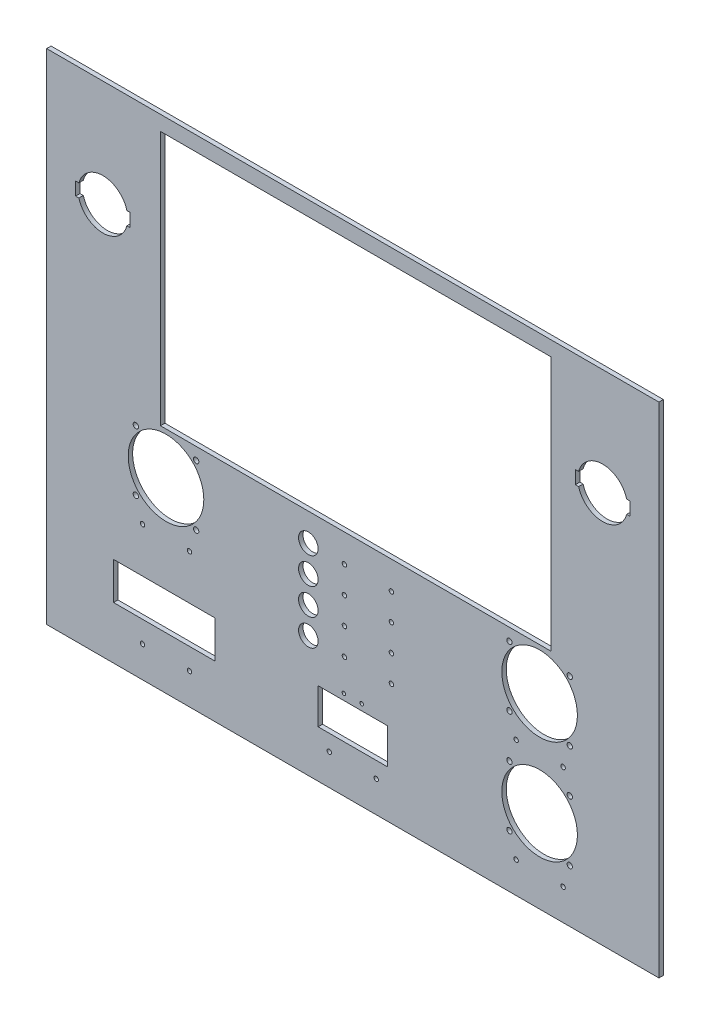
SolidWorks part; units mm, degrees
material "PE High Density"
ref_plane "Front Plane" through (0, 0, 0) normal (0, 0, 1) x (1, 0, 0)
ref_plane "Top Plane" through (0, 0, 0) normal (0, 1, 0) x (1, 0, 0)
ref_plane "Right Plane" through (0, 0, 0) normal (1, 0, 0) x (0, 0, -1)
sketch "Sketch1" plane through (0, 0, 0) normal (0, 0, 1) x (1, 0, 0)
  line L8 (-5.2959, -714.9465) -> (868.8959, -714.9465)
  line L9 (-5.2959, -2.8321) -> (868.8959, -2.8321)
  line L10 (-5.2959, -2.8321) -> (-5.2959, -714.9465)
  line L11 (868.8959, -714.9465) -> (868.8959, -2.8321)
  dimension "D1" = 712.1144
  dimension "D2" = 874.1918
  dimension "D3" = 2.8321
  dimension "D4" = 5.2959
extrude "Boss-Extrude1" add sketch "Sketch1" along normal blind 6.35
sketch "Sketch2" plane through (0, 0, 6.35) normal (0, 0, 1) x (1, 0, 0)
  line L0 (-5.2959, -714.9465) -> (868.8959, -714.9465) construction
  line L1 (868.8959, -714.9465) -> (868.8959, -2.8321) construction
  circle A0 centre (165.1381, -448.3735) radius 53.975
  circle A1 centre (698.5381, -448.3735) radius 53.975
  circle A2 centre (698.5381, -596.4555) radius 53.975
  dimension "D5" = 107.95
  dimension "D1" = 148.082
  dimension "D2" = 118.491
  dimension "D3" = 170.3578
  dimension "D4" = 533.4
extrude "Cut-Extrude1" cut sketch "Sketch2" against normal through all
sketch "Sketch3" plane through (0, 0, 6.35) normal (0, 0, 1) x (1, 0, 0)
  line L0 (-5.2959, -2.8321) -> (-5.2959, -714.9465) construction
  line L1 (-5.2959, -714.9465) -> (868.8959, -714.9465) construction
  circle A0 centre (122.0851, -405.3205) radius 3.81
  circle A2 centre (208.1911, -491.4265) radius 3.81
  circle A3 centre (122.0851, -491.4265) radius 3.81
  circle A4 centre (741.5911, -405.3205) radius 3.81
  circle A5 centre (655.4851, -405.3205) radius 3.81
  circle A6 centre (655.4851, -491.4265) radius 3.81
  circle A7 centre (741.5911, -491.4265) radius 3.81
  circle A8 centre (741.5911, -553.4025) radius 3.81
  circle A9 centre (655.4851, -553.4025) radius 3.81
  circle A10 centre (655.4851, -639.5085) radius 3.81
  circle A11 centre (741.5911, -639.5085) radius 3.81
  circle A12 centre (208.1911, -405.3205) radius 3.81
  dimension "D1" = 7.62
  dimension "D2" = 86.106
  dimension "D3" = 86.106
  dimension "D4" = 127.381
  dimension "D5" = 223.52
  dimension "D6" = 447.294
  dimension "D7" = 86.106
  dimension "D8" = 61.976
  dimension "D9" = 86.106
extrude "Cut-Extrude2" cut sketch "Sketch3" against normal through all
sketch "Sketch4" plane through (0, 0, 6.35) normal (0, 0, 1) x (1, 0, 0)
  line L0 (-5.2959, -714.9465) -> (868.8959, -714.9465) construction
  line L1 (868.8959, -714.9465) -> (868.8959, -2.8321) construction
  circle A0 centre (368.3381, -427.6725) radius 13.97
  circle A1 centre (368.3381, -465.7725) radius 13.97
  circle A2 centre (368.3381, -503.8725) radius 13.97
  circle A3 centre (368.3381, -541.9725) radius 13.97
  dimension "D6" = 27.94
  dimension "D1" = 38.1
  dimension "D2" = 38.1
  dimension "D3" = 38.1
  dimension "D4" = 172.974
  dimension "D5" = 500.5578
extrude "Cut-Extrude3" cut sketch "Sketch4" against normal through all
sketch "Sketch5" plane through (0, 0, 6.35) normal (0, 0, 1) x (1, 0, 0)
  line L0 (-5.2959, -714.9465) -> (868.8959, -714.9465) construction
  line L1 (481.3681, -596.8365) -> (382.3081, -596.8365)
  line L2 (481.3681, -596.8365) -> (481.3681, -647.6365)
  line L3 (481.3681, -647.6365) -> (382.3081, -647.6365)
  line L4 (382.3081, -596.8365) -> (382.3081, -647.6365)
  line L5 (868.8959, -714.9465) -> (868.8959, -2.8321) construction
  dimension "D1" = 99.06
  dimension "D2" = 50.8
  dimension "D3" = 67.31
  dimension "D4" = 387.5278
extrude "Cut-Extrude4" cut sketch "Sketch5" against normal through all
sketch "Sketch6" plane through (0, 0, 6.35) normal (0, 0, 1) x (1, 0, 0)
  line L0 (-5.2959, -2.8321) -> (-5.2959, -714.9465) construction
  line L1 (-5.2959, -714.9465) -> (868.8959, -714.9465) construction
  circle A0 centre (131.6101, -522.4145) radius 3.175
  circle A1 centre (198.6661, -522.4145) radius 3.175
  circle A2 centre (131.6101, -670.4965) radius 3.175
  circle A3 centre (198.6661, -670.4965) radius 3.175
  circle A4 centre (398.3101, -670.4965) radius 3.175
  circle A5 centre (465.3661, -670.4965) radius 3.175
  circle A6 centre (419.9001, -427.9265) radius 3.175
  circle A7 centre (486.9561, -427.9265) radius 3.175
  circle A8 centre (419.9001, -466.0265) radius 3.175
  circle A9 centre (486.9561, -466.0265) radius 3.175
  circle A10 centre (419.9001, -504.1265) radius 3.175
  circle A11 centre (486.9561, -504.1265) radius 3.175
  circle A12 centre (419.9001, -542.2265) radius 3.175
  circle A13 centre (486.9561, -542.2265) radius 3.175
  circle A14 centre (665.0101, -522.4145) radius 3.175
  circle A15 centre (732.0661, -522.4145) radius 3.175
  circle A16 centre (665.0101, -670.4965) radius 3.175
  circle A17 centre (732.0661, -670.4965) radius 3.175
  dimension "D1" = 6.35
  dimension "D2" = 67.056
  dimension "D3" = 148.082
  dimension "D4" = 136.906
  dimension "D5" = 44.45
  dimension "D6" = 199.644
  dimension "D7" = 67.056
  dimension "D8" = 199.644
  dimension "D9" = 67.056
  dimension "D10" = 148.082
  dimension "D11" = 38.1
  dimension "D12" = 38.1
  dimension "D13" = 38.1
  dimension "D14" = 67.056
  dimension "D15" = 178.054
  dimension "D16" = 94.488
extrude "Cut-Extrude5" cut sketch "Sketch6" against normal through all
sketch "Sketch8" plane through (0, 0, 0) normal (0, 0, -1) x (-1, 0, 0)
  line L0 (-868.8959, -2.8321) -> (5.2959, -2.8321) construction
  line L1 (-868.8959, -714.9465) -> (-868.8959, -2.8321) construction
  line L2 (5.2959, -2.8321) -> (5.2959, -714.9465) construction
  line L3 (-109.3272, -145.8341) -> (-114.0206, -145.8341)
  line L4 (-749.5794, -164.6301) -> (-754.2728, -164.6301)
  line L5 (-749.5794, -164.6301) -> (-749.5794, -145.8341)
  line L6 (-749.5794, -145.8341) -> (-754.2728, -145.8341)
  line L7 (-827.5574, -164.6301) -> (-827.5574, -145.8341)
  line L8 (-749.5794, -164.6301) -> (-827.5574, -145.8341) construction
  line L9 (-749.5794, -145.8341) -> (-827.5574, -164.6301) construction
  line L10 (-36.0426, -164.6301) -> (-40.736, -164.6301)
  line L11 (-36.0426, -164.6301) -> (-36.0426, -145.8341)
  line L12 (-36.0426, -145.8341) -> (-40.736, -145.8341)
  line L13 (-114.0206, -164.6301) -> (-114.0206, -145.8341)
  line L14 (-36.0426, -164.6301) -> (-114.0206, -145.8341) construction
  line L15 (-36.0426, -145.8341) -> (-114.0206, -164.6301) construction
  line L16 (-109.3272, -164.6301) -> (-114.0206, -164.6301)
  line L17 (-822.864, -145.8341) -> (-827.5574, -145.8341)
  line L18 (-822.864, -164.6301) -> (-827.5574, -164.6301)
  arc A0 (-822.864, -164.6301) -> (-754.2728, -164.6301) centre (-788.5684, -155.2321) ccw
  arc A1 (-40.736, -145.8341) -> (-109.3272, -145.8341) centre (-75.0316, -155.2321) ccw
  arc A2 (-109.3272, -164.6301) -> (-40.736, -164.6301) centre (-75.0316, -155.2321) ccw
  arc A3 (-754.2728, -145.8341) -> (-822.864, -145.8341) centre (-788.5684, -155.2321) ccw
  dimension "D4" = 71.12
  dimension "D1" = 152.4
  dimension "D2" = 80.3275
  dimension "D3" = 80.3275
  dimension "D5" = 18.796
  dimension "D6" = 77.978
  dimension "D7" = 77.978
extrude "Cut-Extrude7" cut sketch "Sketch8" against normal through all
sketch "Sketch9" plane through (0, 0, 6.35) normal (0, 0, 1) x (1, 0, 0)
  line L0 (90.2081, -586.6765) -> (234.9881, -640.0165) construction
  line L1 (90.2081, -586.6765) -> (234.9881, -586.6765)
  line L2 (90.2081, -586.6765) -> (90.2081, -640.0165)
  line L3 (90.2081, -640.0165) -> (234.9881, -640.0165)
  line L4 (234.9881, -586.6765) -> (234.9881, -640.0165)
  line L5 (234.9881, -586.6765) -> (90.2081, -640.0165) construction
  line L6 (-5.2959, -714.9465) -> (868.8959, -714.9465) construction
  line L10 (-5.2959, -2.8321) -> (-5.2959, -714.9465) construction
  point P4 (162.5981, -613.3465)
  point P9 (-5.2959, -596.8456)
  dimension "D1" = 53.34
  dimension "D2" = 144.78
  dimension "D3" = 101.6
  dimension "D4" = 167.894
extrude "Cut-Extrude8" cut sketch "Sketch9" against normal through all
sketch "Sketch10" plane through (0, 0, 6.35) normal (0, 0, 1) x (1, 0, 0)
  line L1 (157.2641, -23.9555) -> (714.7941, -23.9555)
  line L2 (157.2641, -23.9555) -> (157.2641, -387.9375)
  line L3 (157.2641, -387.9375) -> (714.7941, -387.9375)
  line L4 (714.7941, -23.9555) -> (714.7941, -387.9375)
  line L8 (868.8959, -714.9465) -> (868.8959, -2.8321) construction
  line L9 (868.8959, -2.8321) -> (-5.2959, -2.8321) construction
  dimension "D1" = 557.53
  dimension "D2" = 363.982
  dimension "D3" = 154.1018
  dimension "D4" = 21.1234
extrude "Cut-Extrude9" cut sketch "Sketch10" against normal through all
sketch "Sketch12" plane through (0, 0, 0) normal (0, 0, -1) x (-1, 0, 0)
  line L2 (-481.3681, -647.6365) -> (-481.3681, -596.8365) construction
  line L3 (-481.3681, -596.8365) -> (-382.3081, -596.8365) construction
  circle A0 centre (-444.5381, -587.9465) radius 2.54
  circle A1 centre (-419.1381, -587.9465) radius 2.54
  dimension "D1" = 5.08
  dimension "D2" = 25.4
  dimension "D3" = 36.83
  dimension "D4" = 8.89
extrude "Cut-Extrude11" cut sketch "Sketch12" against normal through all
